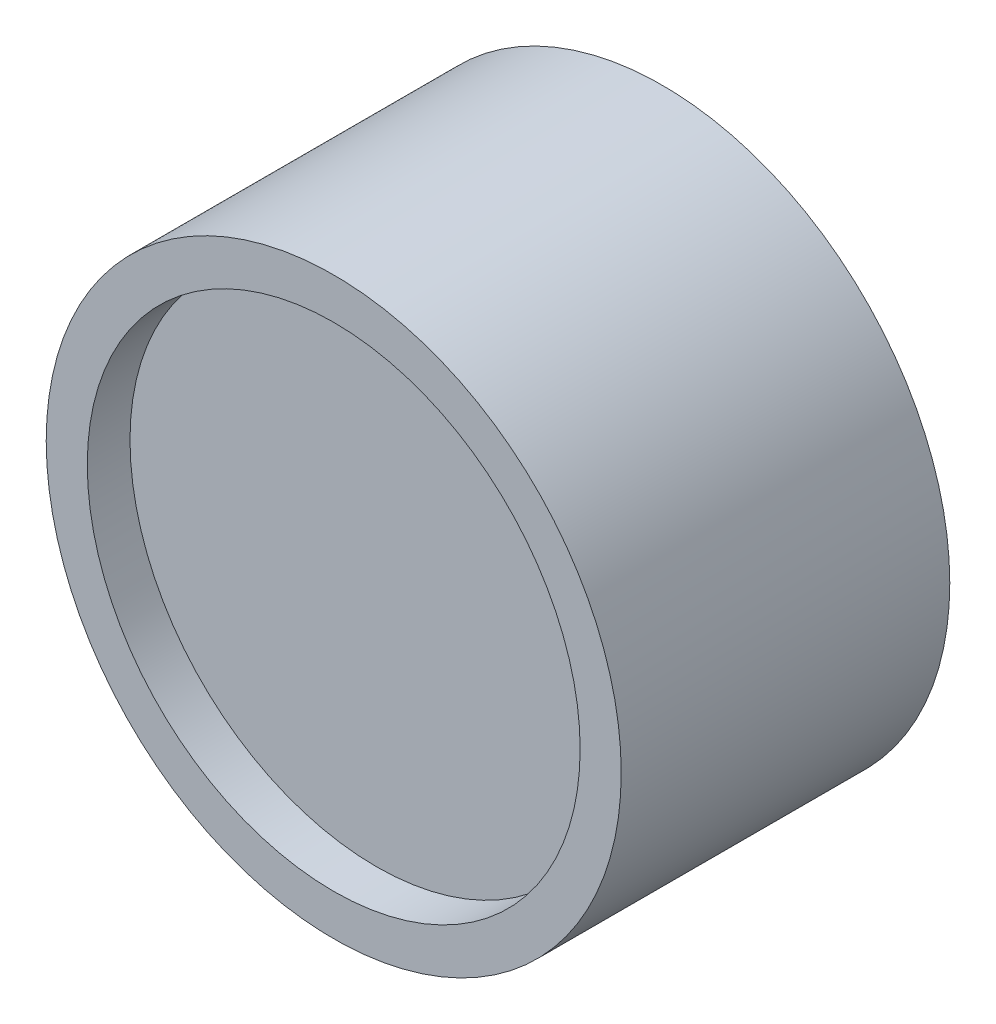
SolidWorks part; units mm, degrees
material "Cast Alloy Steel"
ref_plane "Front Plane" through (0, 0, 0) normal (0, 0, 1) x (1, 0, 0)
ref_plane "Top Plane" through (0, 0, 0) normal (0, 1, 0) x (1, 0, 0)
ref_plane "Right Plane" through (0, 0, 0) normal (1, 0, 0) x (0, 0, -1)
sketch "Sketch1" plane through (0, 0, 0) normal (0, 0, 1) x (1, 0, 0)
  circle A0 centre (0, 0) radius 22.225
  dimension "D1" = 44.45
extrude "Boss-Extrude1" add sketch "Sketch1" along normal blind 25.4
sketch "Sketch2" plane through (0, 0, 25.4) normal (0, 0, 1) x (1, 0, 0)
  circle A0 centre (0, 0) radius 19.05
  dimension "D1" = 38.1
extrude "Cut-Extrude1" cut sketch "Sketch2" against normal blind 3.302 contours A0
sketch "Sketch3" plane through (0, 0, 0) normal (0, 0, -1) x (-1, 0, 0)
  circle A0 centre (0, 0) radius 19.05
  dimension "D1" = 38.1
extrude "Cut-Extrude2" cut sketch "Sketch3" against normal blind 3.302
ref_plane "Plane1" through (0, -22.225, 0) normal (0, 1, 0) x (1, 0, 0)
hole_wizard "3/8 (0.125) Diameter Hole1" positions "Sketch5" profile "Sketch6" hole size "3/8" standard "ANSI Inch"
sketch "Sketch5" plane through (0, -22.225, 0) normal (0, 1, 0) x (1, 0, 0)
  line L0 (-22.225, 0) -> (-22.225, -25.4) construction
  line L2 (22.225, 0) -> (-22.225, 0) construction
  point P0 (0, -12.7)
  dimension "D1" = 22.225
  dimension "D2" = 12.7
sketch "Sketch6" plane through (0, -22.225, 12.7) normal (1, 0, 0) x (0, 0, -1)
  line L0 (0, 0) -> (0, 16.9559)
  line L1 (0, 16.9559) -> (1.5875, 16.002)
  line L2 (1.5875, 16.002) -> (1.5875, 0)
  line L5 (1.5875, 0) -> (0, 0)
  line L10 (0, 16.9559) -> (-1.5875, 16.002) construction
  line L11 (0, -6.35) -> (0, 107.95) construction
  dimension "Hole Dia." = 3.175
  dimension "Hole Depth" = 16.002
  dimension "Drill Angle" = 118
